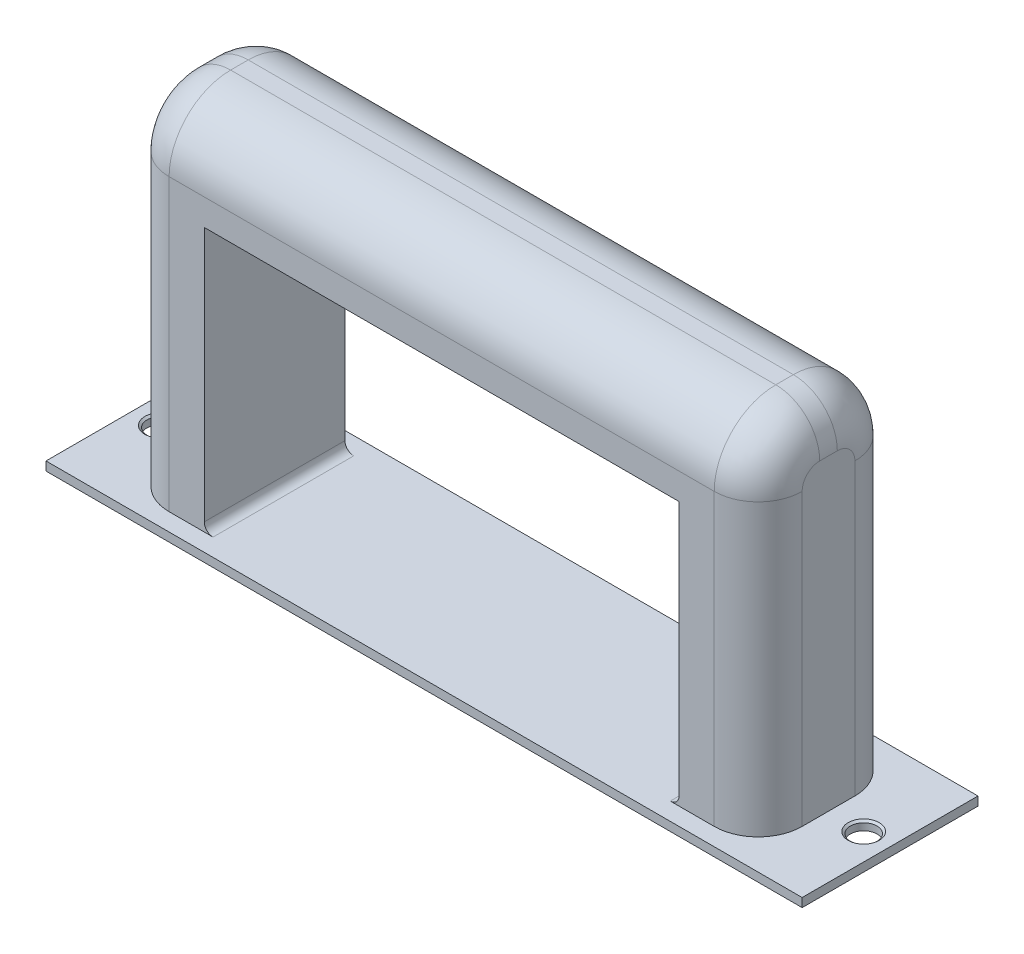
SolidWorks part; units mm, degrees
material "Galvanized Steel"
ref_plane "Front Plane" through (0, 0, 0) normal (0, 0, 1) x (1, 0, 0)
ref_plane "Top Plane" through (0, 0, 0) normal (0, 1, 0) x (1, 0, 0)
ref_plane "Right Plane" through (0, 0, 0) normal (1, 0, 0) x (0, 0, -1)
sketch "Sketch2" plane through (0, 0, 0) normal (0, 1, 0) x (1, 0, 0)
  line L0 (109.22, 50.8) -> (109.22, 0) construction
  line L1 (0, 0) -> (218.44, 0)
  line L2 (0, 0) -> (0, 50.8)
  line L3 (0, 50.8) -> (218.44, 50.8)
  line L4 (218.44, 0) -> (218.44, 50.8)
  line L5 (0, 25.4) -> (218.44, 25.4) construction
  circle A0 centre (7.62, 25.4) radius 3.81
  circle A1 centre (210.82, 25.4) radius 3.81
  dimension "D3" = 7.62
  dimension "D1" = 203.2
  dimension "D2" = 50.8
  dimension "D4" = 7.62
extrude "Boss-Extrude1" add sketch "Sketch2" along normal blind 2.54
sketch "Sketch3" plane through (0, 2.54, 0) normal (0, 1, 0) x (1, 0, 0)
  line L0 (0, 45.72) -> (218.44, 45.72) construction
  line L1 (0, 50.8) -> (0, 0) construction
  line L2 (218.44, 0) -> (218.44, 50.8) construction
  line L3 (0, 5.08) -> (218.44, 5.08) construction
  line L4 (218.44, 50.8) -> (0, 50.8) construction
  line L5 (0, 0) -> (218.44, 0) construction
  line L7 (17.78, 45.72) -> (200.66, 45.72)
  line L8 (17.78, 45.72) -> (17.78, 5.08)
  line L9 (17.78, 5.08) -> (200.66, 5.08)
  line L10 (200.66, 45.72) -> (200.66, 5.08)
  dimension "D1" = 5.08
  dimension "D2" = 5.08
  dimension "D3" = 17.78
  dimension "D4" = 17.78
extrude "Boss-Extrude2" add sketch "Sketch3" along normal blind 101.6
sketch "Sketch5" plane through (0, 0, -5.08) normal (0, 0, 1) x (1, 0, 0)
  line L0 (109.22, 104.14) -> (109.22, 2.54) construction
  line L1 (17.78, 104.14) -> (200.66, 104.14) construction
  line L2 (0, 2.54) -> (218.44, 2.54) construction
  line L3 (17.78, 2.54) -> (200.66, 2.54) construction
  line L4 (40.64, 2.54) -> (177.8, 2.54)
  line L5 (40.64, 2.54) -> (40.64, 78.74)
  line L6 (40.64, 78.74) -> (177.8, 78.74)
  line L7 (177.8, 2.54) -> (177.8, 78.74)
  dimension "D1" = 68.58
  dimension "D2" = 68.58
  dimension "D3" = 25.4
extrude "Cut-Extrude2" cut sketch "Sketch5" against normal blind 101.6 contours L5 L4 L7 L6
fillet "Fillet1" radius 17.78 1 edges at (109.22, 104.14, -5.08)
fillet "Fillet2" radius 17.78 1 edges at (109.22, 104.14, -45.72)
fillet "Fillet3" radius 12.7 5 edges at (17.78, 44.45, -5.08) (17.78, 98.9324, -10.2876) (17.78, 104.14, -25.4) (17.78, 44.45, -45.72) (17.78, 98.9324, -40.5124)
fillet "Fillet4" radius 12.7 5 edges at (200.66, 104.14, -25.4) (200.66, 44.45, -5.08) (200.66, 98.9324, -10.2876) (200.66, 44.45, -45.72) (200.66, 98.9324, -40.5124)
fillet "Fillet5" radius 2.54 1 edges at (40.64, 2.54, -25.4)
fillet "Fillet6" radius 2.54 1 edges at (177.8, 2.54, -25.4)
hole_wizard "N (0.302) Diameter Hole1" positions "3DSketch1" profile "Sketch7" hole size "N" standard "ANSI Inch" end condition through all
sketch3d "3DSketch1"
  line L0 (210.82, 2.54, -25.4) -> (210.82, 0, -25.4) construction
  line L1 (7.62, 2.54, -25.4) -> (7.62, 0, -25.4) construction
  point P0 (210.82, 2.54, -25.4)
  point P4 (7.62, 2.54, -25.4)
sketch "Sketch7" plane through (210.82, 2.54, -25.4) normal (1, 0, 0) x (0, 0, 1)
  line L0 (0, 0) -> (0, 2.54)
  line L1 (0, 2.54) -> (3.8354, 2.54)
  line L2 (3.8354, 2.54) -> (3.8354, 0.5328)
  line L3 (3.8354, 0.5328) -> (4.4704, 0)
  line L5 (4.4704, 0) -> (0, 0)
  line L6 (-3.8354, 0.5328) -> (-4.4704, 0) construction
  line L11 (0, -6.35) -> (0, 107.95) construction
  dimension "Thru Hole Dia." = 7.6708
  dimension "Thru Hole Depth" = 2.54
  dimension "Near C'Sink Dia." = 8.9408
  dimension "Near C'Sink Angle" = 100
